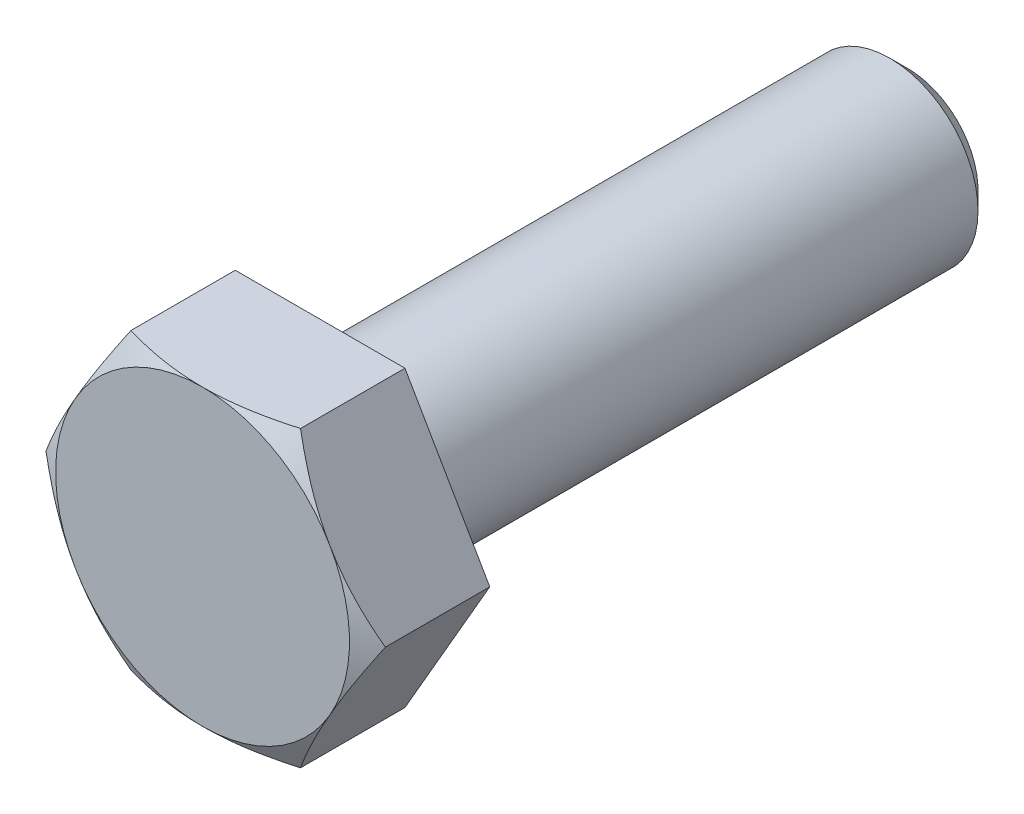
SolidWorks part; units mm, degrees
ref_plane "Plane1" through (0, 0, 0) normal (0, 0, 1) x (1, 0, 0)
ref_plane "MSC_PF1" through (0, 0, 0) normal (0, 1, 0) x (1, 0, 0)
ref_plane "Plane3" through (0, 0, 0) normal (1, 0, 0) x (0, 0, -1)
sketch "Sketch1" plane through (0, 0, 0) normal (0, 0, 1) x (1, 0, 0)
  line L0 (0, 0) -> (1, 0) construction
  line L1 (-2.8868, 5) -> (2.8868, 5)
  line L2 (-2.8868, -5) -> (2.8868, -5)
  line L3 (2.8868, 5) -> (5.7735, 0)
  line L4 (5.7735, 0) -> (2.8868, -5)
  line L5 (-2.8868, 5) -> (-5.7735, 0)
  line L6 (-5.7735, 0) -> (-2.8868, -5)
  circle A0 centre (0, 0) radius 5 construction
  dimension "P" = 1
  dimension "s" = 10
extrude "Base-Extrude" add sketch "Sketch1" along normal blind 4
sketch "Sketch5" plane through (0, 0, 0) normal (0, 1, 0) x (1, 0, 0)
  line L0 (0, 0) -> (0, -62.6881) construction
  line L1 (-5.7735, -4) -> (-5, -4)
  line L2 (-5, -4) -> (-5.7735, -3.5534)
  line L3 (-5.7735, -4) -> (-5.7735, 0) construction
  line L4 (-5.7735, -3.5534) -> (-5.7735, -4)
  dimension "D1" = 30
  dimension "D2" = 5
revolve "Cut-Revolve1" cut sketch "Sketch5" angle 360 about L0
sketch "Sketch3" plane through (0, 0, 0) normal (0, 0, -1) x (-1, 0, 0)
  circle A0 centre (0, 0) radius 3
  dimension "_d" = 6
extrude "Boss-Extrude1" add sketch "Sketch3" along normal blind 20
cosmetic thread "Cosmetic Thread1"
chamfer "Chamfer1" distance 0.6134 angle 45 1 edges at (-3, 0, -20)
fillet "Fillet1" radius 0.25 1 edges at (3, 0, 0)
equation "\"D2@Sketch5\" = \"s@Sketch1\" / 2"
equation "\"D2@Cosmetic Thread1\" = \"_d@Sketch3\" - 2 * 0.6134 * \"P@Sketch1\""
equation "\"D1@Chamfer1\" =  ( \"_d@Sketch3\" - \"D2@Cosmetic Thread1\" )  / 2"
